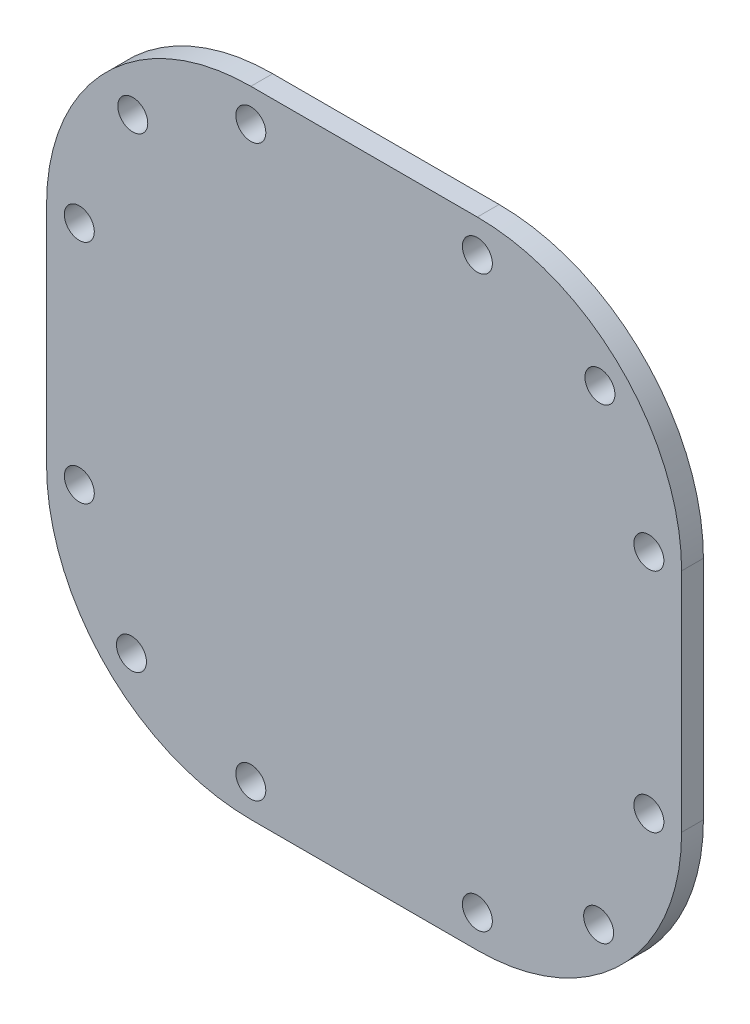
SolidWorks part; units mm, degrees
material "Acrylic (Medium-high impact)"
ref_plane "Front Plane" through (0, 0, 0) normal (0, 0, 1) x (1, 0, 0)
ref_plane "Top Plane" through (0, 0, 0) normal (0, 1, 0) x (1, 0, 0)
ref_plane "Right Plane" through (0, 0, 0) normal (1, 0, 0) x (0, 0, -1)
sketch "Sketch1" plane through (0, 0, 0) normal (0, 0, 1) x (1, 0, 0)
  line L1 (46.5772, -47.371) -> (-46.5773, -47.371)
  line L2 (47.371, -46.5773) -> (47.371, 46.5772)
  line L3 (46.5772, 47.371) -> (-46.5773, 47.371)
  line L4 (-47.371, -46.5773) -> (-47.371, 46.5772)
  line L5 (47.371, -47.371) -> (-47.371, 47.371) construction
  line L6 (47.371, 47.371) -> (-47.371, -47.371) construction
  arc A1 (-47.371, 46.5772) -> (-46.5773, 47.371) centre (-46.5773, 46.5772) cw
  arc A2 (46.5772, 47.371) -> (47.371, 46.5772) centre (46.5772, 46.5772) cw
  arc A3 (47.371, -46.5773) -> (46.5772, -47.371) centre (46.5772, -46.5773) cw
  arc A4 (-46.5773, -47.371) -> (-47.371, -46.5773) centre (-46.5773, -46.5773) cw
  point P2 (0, 0)
  dimension "D1" = 0.7937
  dimension "D2" = 94.742
extrude "Boss-Extrude1" add sketch "Sketch1" along normal blind 3.175
sketch "Sketch3" plane through (0, 0, 3.175) normal (0, 0, 1) x (1, 0, 0)
  circle A0 centre (16.49, -41.463) radius 2.1828 construction
  circle A1 centre (34.1474, -34.1474) radius 2.1828 construction
  circle A2 centre (41.4607, -16.4945) radius 2.1828 construction
  circle A3 centre (41.4607, 16.49) radius 2.1828 construction
  circle A4 centre (34.3356, 33.8693) radius 2.1828 construction
  circle A5 centre (16.4922, 41.4607) radius 2.1828 construction
  circle A6 centre (-16.4922, 41.4607) radius 2.1828 construction
  circle A7 centre (-33.6811, 34.0575) radius 2.1828 construction
  circle A8 centre (-41.463, 16.4922) radius 2.1828 construction
  circle A9 centre (-41.463, -16.4922) radius 2.1828 construction
  circle A10 centre (-16.4945, -41.463) radius 2.1828 construction
  circle A11 centre (-33.8693, -33.9592) radius 2.1828 construction
  circle A12 centre (16.49, -41.463) radius 2.1828
  circle A13 centre (34.1474, -34.1474) radius 2.1828
  circle A14 centre (41.4607, -16.4945) radius 2.1828
  circle A15 centre (41.4607, 16.49) radius 2.1828
  circle A16 centre (34.3356, 33.8693) radius 2.1828
  circle A17 centre (16.4922, 41.4607) radius 2.1828
  circle A18 centre (-16.4922, 41.4607) radius 2.1828
  circle A19 centre (-33.6811, 34.0575) radius 2.1828
  circle A20 centre (-41.463, 16.4922) radius 2.1828
  circle A21 centre (-41.463, -16.4922) radius 2.1828
  circle A22 centre (-16.4945, -41.463) radius 2.1828
  circle A23 centre (-33.8693, -33.9592) radius 2.1828
extrude "Cut-Extrude2" cut sketch "Sketch3" against normal up to next
sketch "Sketch4" plane through (0, 0, 3.175) normal (0, 0, 1) x (1, 0, 0)
  line L1 (16.4846, -46.228) -> (-16.4846, -46.228)
  line L2 (46.228, -16.4846) -> (46.228, 16.4846)
  line L3 (16.4846, 46.228) -> (-16.4846, 46.228)
  line L4 (-46.228, -16.4846) -> (-46.228, 16.4846)
  line L5 (46.228, -46.228) -> (-46.228, 46.228) construction
  line L6 (46.228, 46.228) -> (-46.228, -46.228) construction
  line L7 (54.7956, -64.0487) -> (-54.7956, -64.0487)
  line L8 (54.7956, -64.0487) -> (54.7956, 64.0487)
  line L9 (54.7956, 64.0487) -> (-54.7956, 64.0487)
  line L10 (-54.7956, -64.0487) -> (-54.7956, 64.0487)
  line L11 (54.7956, -64.0487) -> (-54.7956, 64.0487) construction
  line L12 (54.7956, 64.0487) -> (-54.7956, -64.0487) construction
  arc A0 (-46.228, 16.4846) -> (-16.4846, 46.228) centre (-16.4846, 16.4846) cw
  arc A1 (16.4846, 46.228) -> (46.228, 16.4846) centre (16.4846, 16.4846) cw
  arc A2 (46.228, -16.4846) -> (16.4846, -46.228) centre (16.4846, -16.4846) cw
  arc A3 (-16.4846, -46.228) -> (-46.228, -16.4846) centre (-16.4846, -16.4846) cw
  point P0 (0, 0)
  point P6 (0, 0)
  dimension "D2" = 29.7434
  dimension "D1" = 92.456
extrude "Cut-Extrude3" cut sketch "Sketch4" against normal through all
